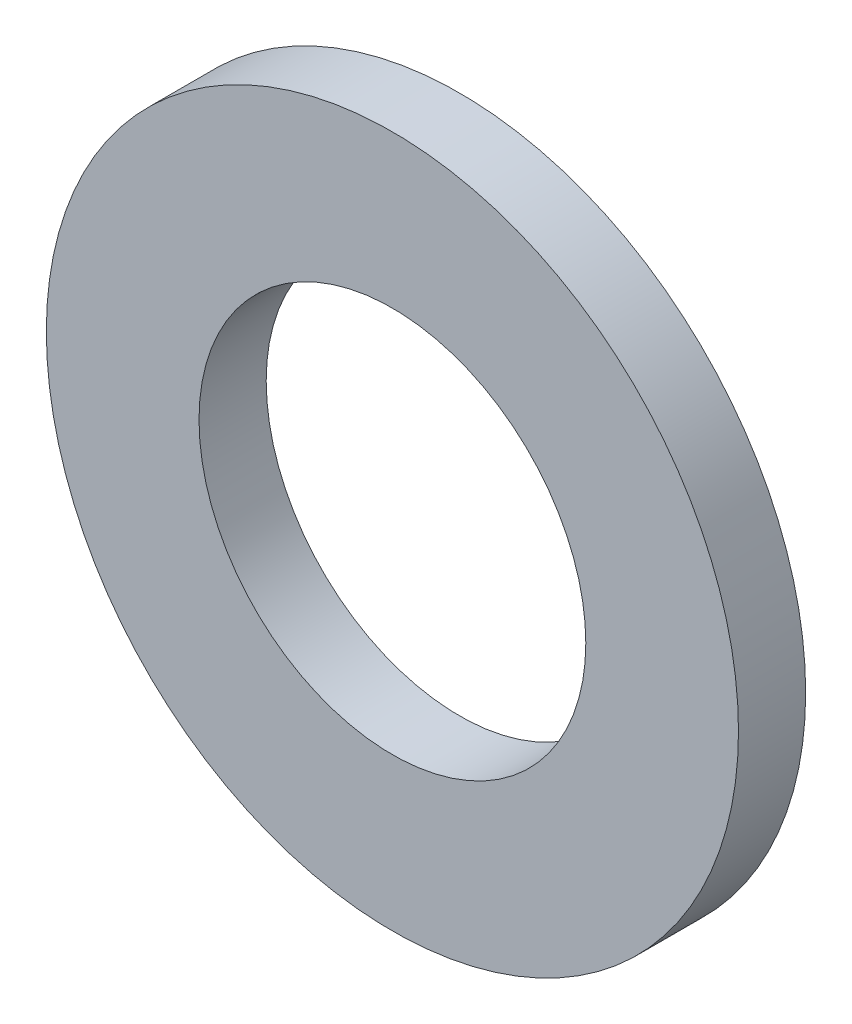
SolidWorks part; units mm, degrees
ref_plane "Front Plane" through (0, 0, 0) normal (0, 0, 1) x (1, 0, 0)
ref_plane "Top Plane" through (0, 0, 0) normal (0, 1, 0) x (1, 0, 0)
ref_plane "Right Plane" through (0, 0, 0) normal (1, 0, 0) x (0, 0, -1)
sketch "Sketch1" plane through (0, 0, 0) normal (0, 0, 1) x (1, 0, 0)
  circle A0 centre (0, 0) radius 9.5
  circle A1 centre (0, 0) radius 17
  dimension "D1" = 19
  dimension "D2" = 34
extrude "Boss-Extrude1" add sketch "Sketch1" along normal blind 3.3
